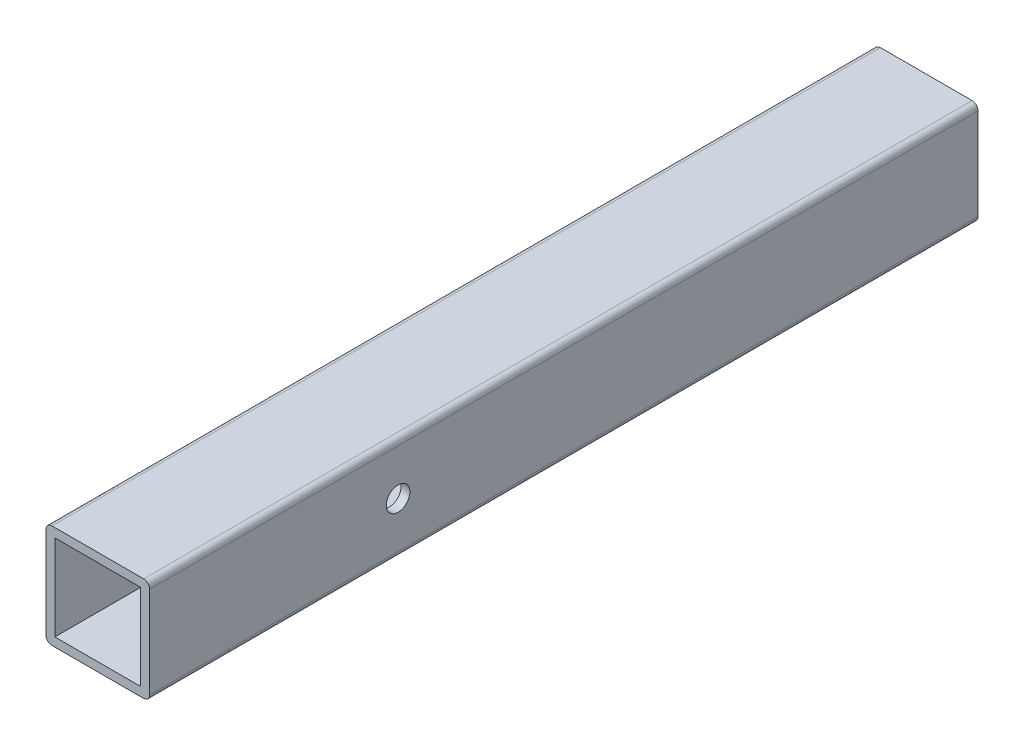
SolidWorks part; units mm, degrees
ref_plane "Front" through (0, 0, 0) normal (0, 0, 1) x (1, 0, 0)
ref_plane "Top" through (0, 0, 0) normal (0, 1, 0) x (1, 0, 0)
ref_plane "Right" through (0, 0, 0) normal (1, 0, 0) x (0, 0, -1)
sketch "Sketch1" plane through (0, 0, 0) normal (0, 0, 1) x (1, 0, 0)
  line L1 (-17.5, -17.5) -> (17.5, -17.5)
  line L2 (-17.5, -17.5) -> (-17.5, 17.5)
  line L3 (-17.5, 17.5) -> (17.5, 17.5)
  line L4 (17.5, -17.5) -> (17.5, 17.5)
  line L5 (-17.5, -17.5) -> (17.5, 17.5) construction
  line L6 (-17.5, 17.5) -> (17.5, -17.5) construction
  point P0 (0, 0)
  dimension "D1" = 35
  dimension "D2" = 35
extrude "Extrude-Thin1" add sketch "Sketch1" along normal blind 140 and the other way blind 140 thin thin type one direction reverse wall 3
fillet "Fillet1" radius 2 4 edges at (17.5, -17.5, 0) (-17.5, -17.5, 0) (-17.5, 17.5, 0) (17.5, 17.5, 0)
sketch "Sketch2" plane through (17.5, 0, 0) normal (1, 0, 0) x (0, 0, -1)
  line L0 (-140, -15.5) -> (-140, 15.5) construction
  circle A0 centre (-56, 0) radius 4
  dimension "D1" = 8
  dimension "D2" = 84
extrude "Cut-Extrude1" cut sketch "Sketch2" against normal blind 40
